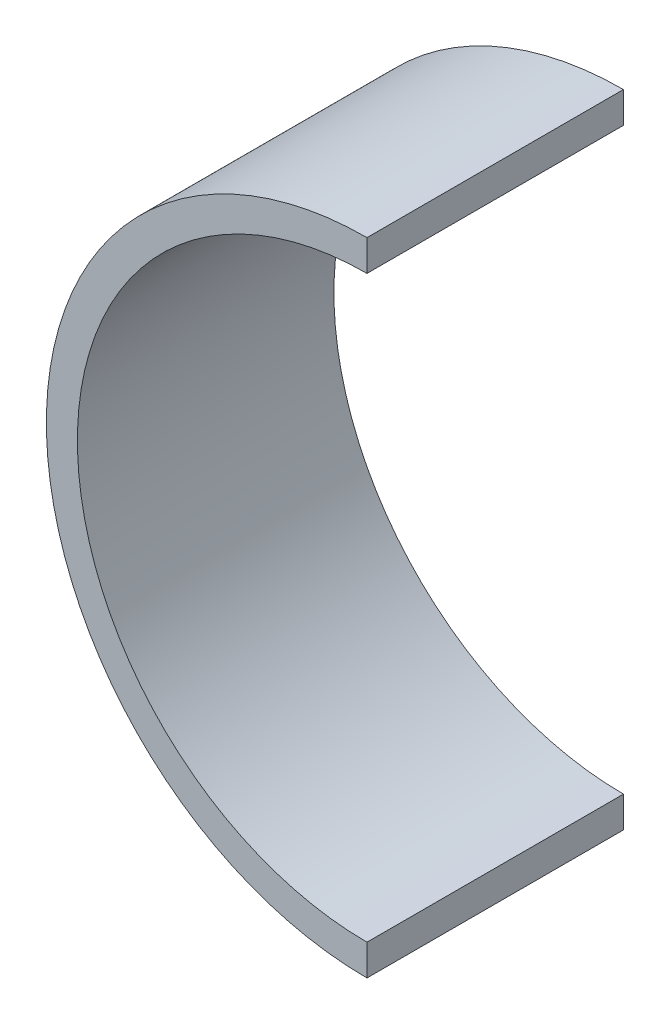
SolidWorks part; units mm, degrees
ref_plane "Front Plane" through (0, 0, 0) normal (0, 0, 1) x (1, 0, 0)
ref_plane "Top Plane" through (0, 0, 0) normal (0, 1, 0) x (1, 0, 0)
ref_plane "Right Plane" through (0, 0, 0) normal (1, 0, 0) x (0, 0, -1)
sketch "Sketch2" plane through (0, 0, 0) normal (0, 0, 1) x (1, 0, 0)
  line L0 (0, 310) -> (0, 280)
  line L1 (0, -280) -> (0, -310)
  arc A0 (0, 310) -> (0, -310) centre (0, 0) ccw
  arc A1 (0, 280) -> (0, -280) centre (0, 0) ccw
  arc A2 (0, 310) -> (0, -310) centre (0, 0) ccw construction
  dimension "D1" = 560
extrude "Boss-Extrude1" add sketch "Sketch2" along normal up to vertex (124 mm away) and the other way up to vertex (124 mm away)
